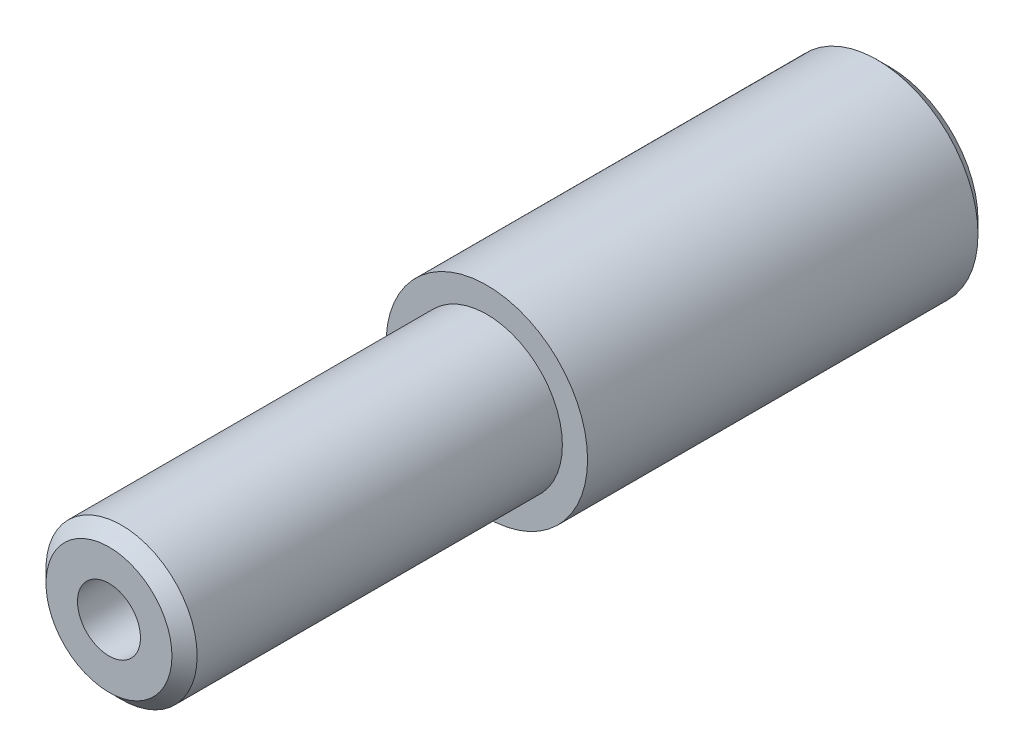
SolidWorks part; units mm, degrees
ref_plane "Front Plane" through (0, 0, 0) normal (0, 0, 1) x (1, 0, 0)
ref_plane "Top Plane" through (0, 0, 0) normal (0, 1, 0) x (1, 0, 0)
ref_plane "Right Plane" through (0, 0, 0) normal (1, 0, 0) x (0, 0, -1)
sketch "Sketch1" plane through (0, 0, 0) normal (0, 0, 1) x (1, 0, 0)
  circle A0 centre (-161.2297, -61.0733) radius 4
extrude "Boss-Extrude1" add sketch "Sketch1" along normal blind 16
sketch "Sketch2" plane through (0, 0, 16) normal (0, 0, 1) x (1, 0, 0)
  circle A0 centre (-161.2297, -61.0733) radius 3
extrude "Boss-Extrude2" add sketch "Sketch2" along normal blind 15
sketch "Sketch3" plane through (0, 0, 31) normal (0, 0, 1) x (1, 0, 0)
  circle A0 centre (-161.2297, -61.0733) radius 1.25
extrude "Cut-Extrude1" cut sketch "Sketch3" against normal blind 40
cosmetic thread "Cosmetic Thread1" parameters "D2"=3
chamfer "Chamfer1" distance 0.5 angle 45 2 edges at (-157.2297, -61.0733, 0) (-158.2297, -61.0733, 31)
